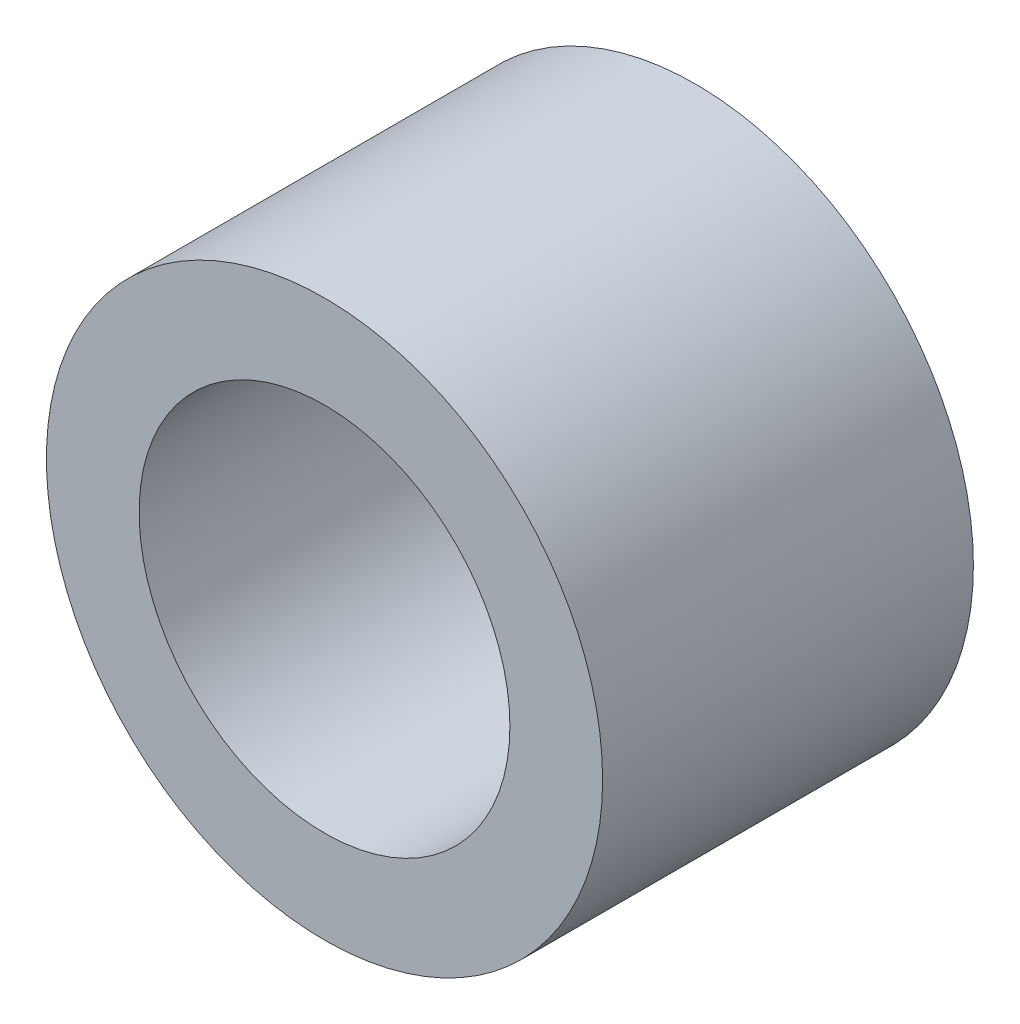
SolidWorks part; units mm, degrees
ref_plane "Front Plane" through (0, 0, 0) normal (0, 0, 1) x (1, 0, 0)
ref_plane "Top Plane" through (0, 0, 0) normal (0, 1, 0) x (1, 0, 0)
ref_plane "Right Plane" through (0, 0, 0) normal (1, 0, 0) x (0, 0, -1)
sketch "Sketch1" plane through (0, 0, 0) normal (0, 0, 1) x (1, 0, 0)
  circle A0 centre (0, 0) radius 6.35
  circle A1 centre (0, 0) radius 9.525
  dimension "D1" = 12.7
  dimension "D2" = 19.05
extrude "Boss-Extrude1" add sketch "Sketch1" along normal blind 12.7
